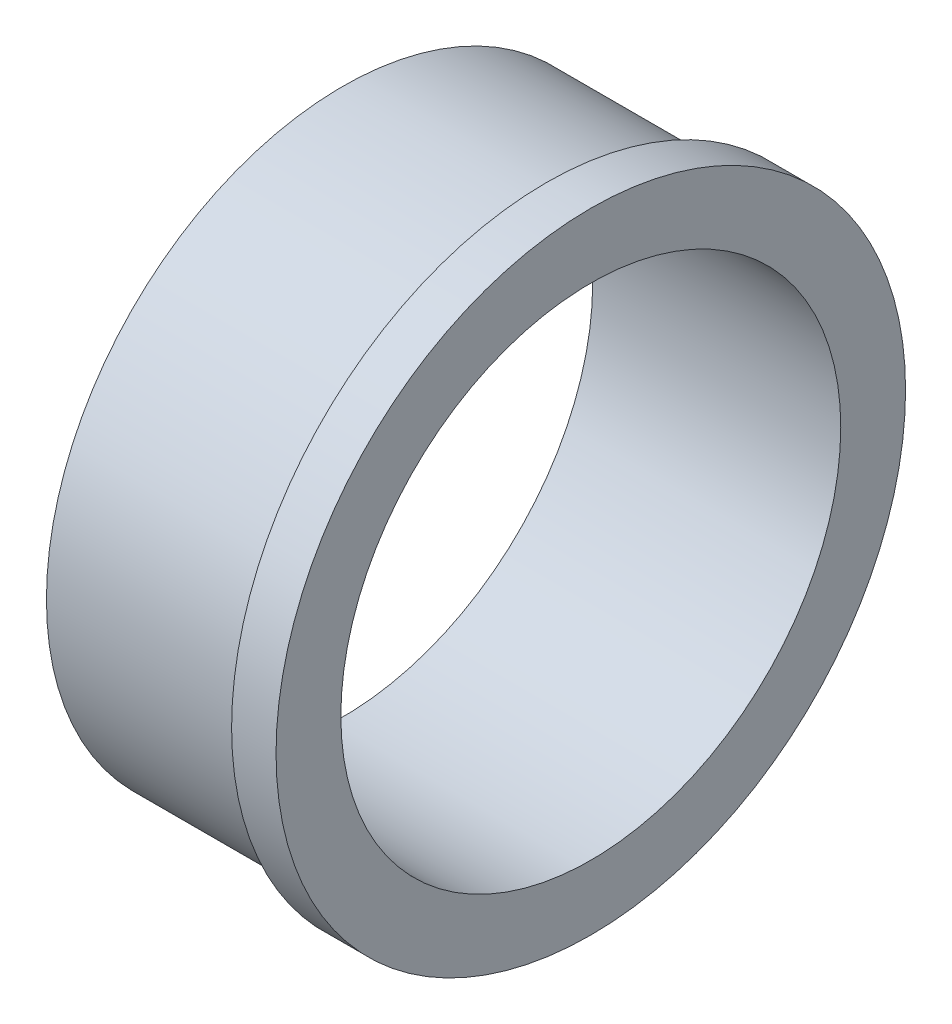
SolidWorks part; units mm, degrees
ref_plane "Plan de face" through (0, 0, 0) normal (0, 0, 1) x (1, 0, 0)
ref_plane "Plan de dessus" through (0, 0, 0) normal (0, 1, 0) x (1, 0, 0)
ref_plane "Plan de droite" through (0, 0, 0) normal (1, 0, 0) x (0, 0, -1)
sketch "Esquisse1" plane through (0, 0, 0) normal (0, 0, 1) x (1, 0, 0)
  line L0 (0, 0) -> (19.8271, 0) construction
  line L1 (0, 10.125) -> (10.05, 10.125)
  line L2 (10.05, 10.125) -> (10.05, 12.75)
  line L3 (10.05, 12.75) -> (8.25, 12.75)
  line L4 (8.25, 12.75) -> (8.25, 12)
  line L5 (8.25, 12) -> (0, 12)
  line L6 (0, 12) -> (0, 10.125)
  dimension "D1" = 20.25
  dimension "D2" = 24
  dimension "D3" = 25.5
  dimension "D4" = 8.25
  dimension "D5" = 1.8
revolve "Révolution1" add sketch "Esquisse1" angle 360 about L0
